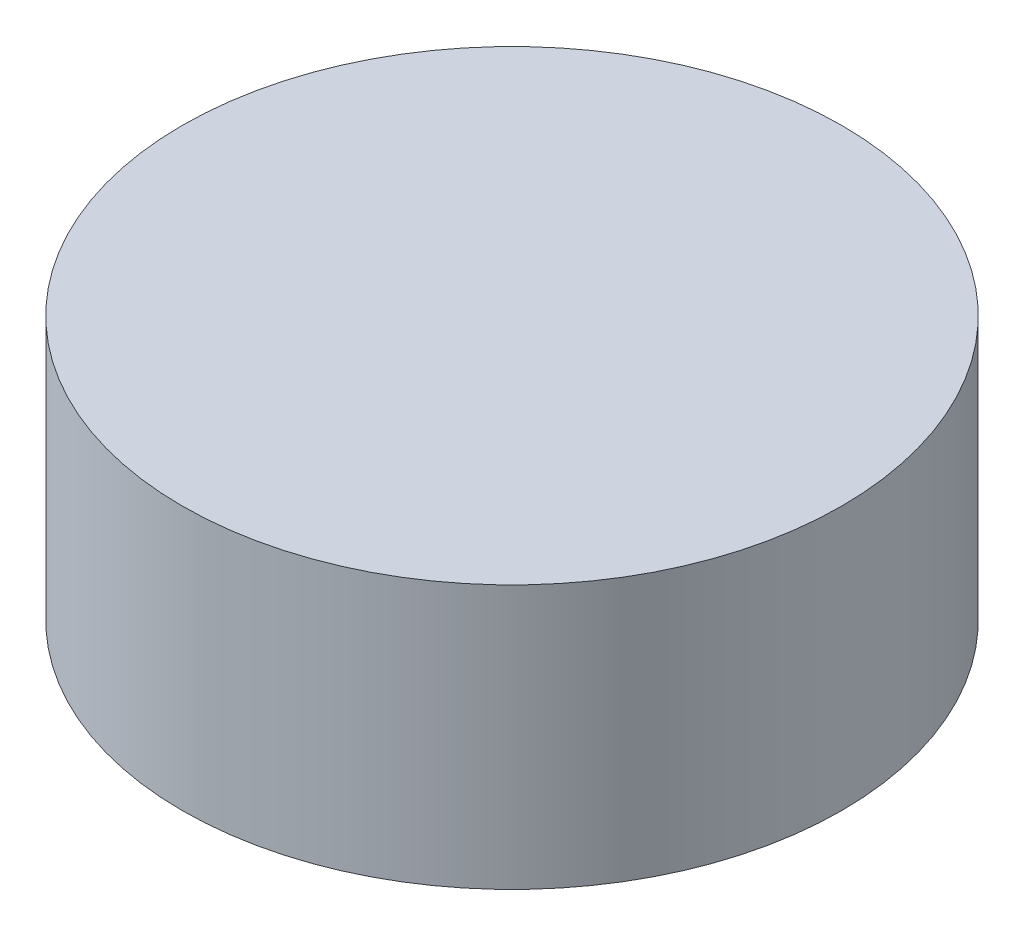
SolidWorks part; units mm, degrees
ref_plane "Alzado" through (0, 0, 0) normal (0, 0, 1) x (1, 0, 0)
ref_plane "Planta" through (0, 0, 0) normal (0, 1, 0) x (1, 0, 0)
ref_plane "Vista lateral" through (0, 0, 0) normal (1, 0, 0) x (0, 0, -1)
sketch "Croquis1" plane through (0, 0, 0) normal (0, 1, 0) x (1, 0, 0)
  circle A0 centre (0, 0) radius 2.5
  dimension "D1" = 5
extrude "Saliente-Extruir1" add sketch "Croquis1" along normal blind 2
